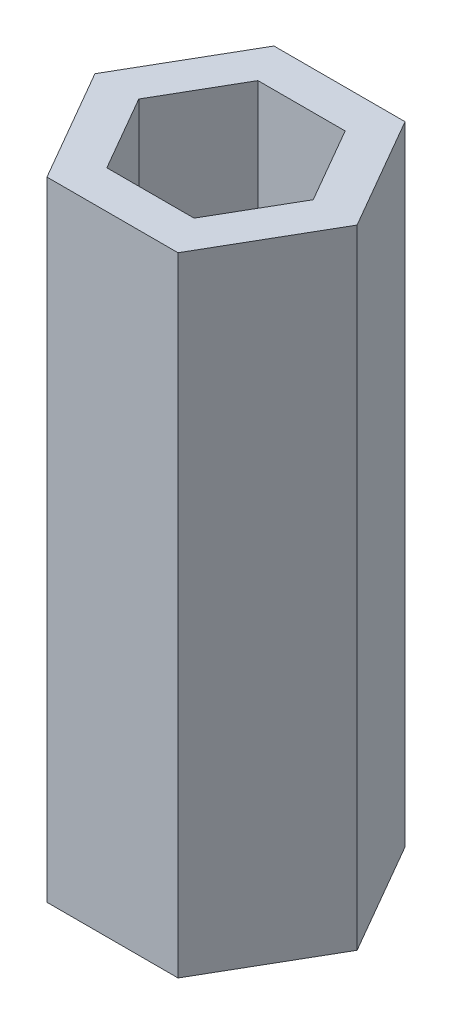
SolidWorks part; units mm, degrees
ref_plane "Front Plane" through (0, 0, 0) normal (0, 0, 1) x (1, 0, 0)
ref_plane "Top Plane" through (0, 0, 0) normal (0, 1, 0) x (1, 0, 0)
ref_plane "Right Plane" through (0, 0, 0) normal (1, 0, 0) x (0, 0, -1)
sketch "Sketch1" plane through (0, 0, 0) normal (0, 1, 0) x (1, 0, 0)
  line L1 (4.0988, 0) -> (2.0494, 3.5496)
  line L2 (2.0494, 3.5496) -> (-2.0494, 3.5496)
  line L3 (-2.0494, 3.5496) -> (-4.0988, 0)
  line L4 (-4.0988, 0) -> (-2.0494, -3.5497)
  line L5 (-2.0494, -3.5497) -> (2.0494, -3.5496)
  line L6 (2.0494, -3.5496) -> (4.0988, 0)
  line L7 (6.1592, 0) -> (3.0796, 5.334)
  line L8 (3.0796, 5.334) -> (-3.0796, 5.334)
  line L9 (-3.0796, 5.334) -> (-6.1592, 0)
  line L10 (-6.1592, 0) -> (-3.0796, -5.334)
  line L11 (-3.0796, -5.334) -> (3.0796, -5.334)
  line L12 (3.0796, -5.334) -> (6.1592, 0)
  circle A0 centre (0, 0) radius 3.5497 construction
  circle A1 centre (0, 0) radius 5.334 construction
  dimension "D1" = 7.0993
  dimension "D2" = 10.668
extrude "Boss-Extrude1" add sketch "Sketch1" along normal blind 29.5155
